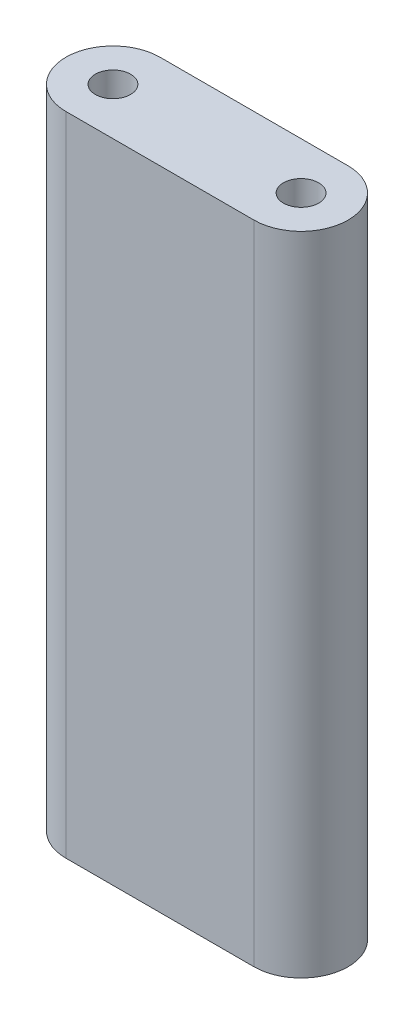
SolidWorks part; units mm, degrees
ref_plane "前视基准面" through (0, 0, 0) normal (0, 0, 1) x (1, 0, 0)
ref_plane "上视基准面" through (0, 0, 0) normal (0, 1, 0) x (1, 0, 0)
ref_plane "右视基准面" through (0, 0, 0) normal (1, 0, 0) x (0, 0, -1)
sketch "草图1" plane through (0, 0, 0) normal (0, 1, 0) x (1, 0, 0)
  line L0 (-10.3736, 0) -> (5.6264, 0) construction
  line L1 (-10.3736, 4) -> (5.6264, 4)
  line L2 (-10.3736, -4) -> (5.6264, -4)
  arc A0 (-10.3736, 4) -> (-10.3736, -4) centre (-10.3736, 0) ccw
  arc A1 (5.6264, -4) -> (5.6264, 4) centre (5.6264, 0) ccw
  circle A2 centre (-10.3736, 0) radius 1.5
  circle A3 centre (5.6264, 0) radius 1.5
  point P3 (-2.3736, 0)
extrude "凸台-拉伸1" add sketch "草图1" along normal blind 55
